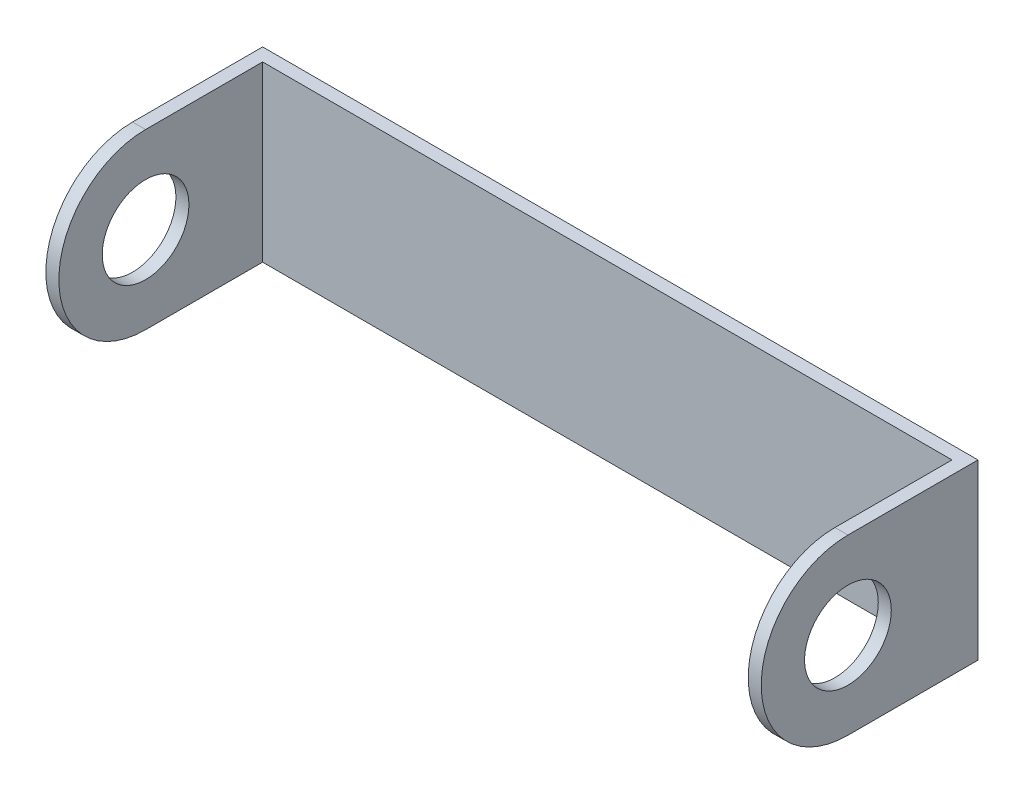
SolidWorks part; units mm, degrees
ref_plane "정면" through (0, 0, 0) normal (0, 0, 1) x (1, 0, 0)
ref_plane "윗면" through (0, 0, 0) normal (0, 1, 0) x (1, 0, 0)
ref_plane "우측면" through (0, 0, 0) normal (1, 0, 0) x (0, 0, -1)
sketch "스케치1" plane through (0, 0, 0) normal (1, 0, 0) x (0, 0, -1)
  line L0 (0, -20) -> (0, 20)
  line L1 (0, 20) -> (-3, 20)
  line L2 (-3, 20) -> (-3, -20)
  line L3 (-3, -20) -> (0, -20)
  point P5 (0, 0)
  dimension "D1" = 3
  dimension "D2" = 40
extrude "보스-돌출1" add sketch "스케치1" along normal mid plane 159
sketch "스케치2" plane through (79.5, 0, 0) normal (1, 0, 0) x (0, 0, -1)
  line L0 (0, 20) -> (-30, 20)
  line L1 (0, -20) -> (-30, -20)
  line L2 (0, 20) -> (0, -20)
  arc A0 (-30, 20) -> (-30, -20) centre (-30, 0) ccw
  circle A1 centre (-30, 0) radius 10
  dimension "D1" = 40
  dimension "D3" = 20
  dimension "D2" = 30
extrude "보스-돌출2" add sketch "스케치2" along normal blind 3
mirror "대칭 복사1" about plane through (0, 0, 0) normal (1, 0, 0) of "보스-돌출2"
